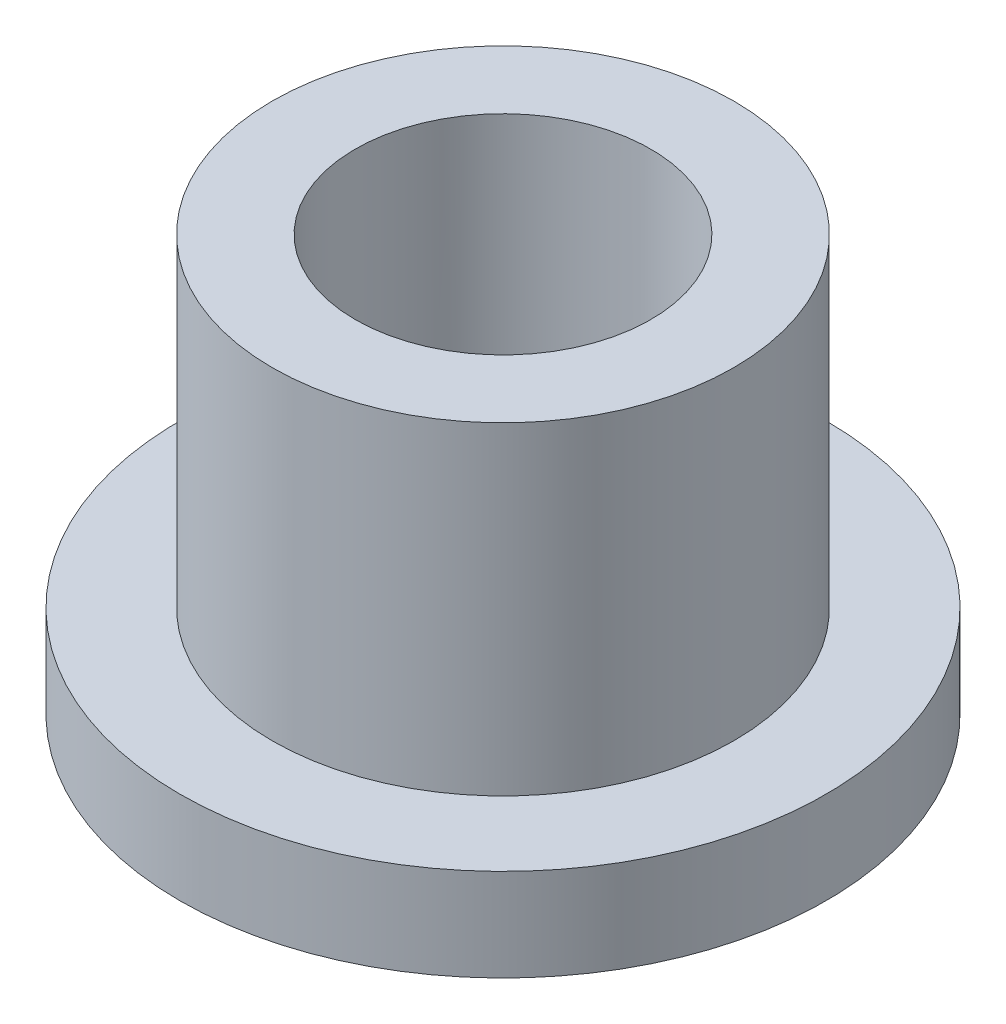
SolidWorks part; units mm, degrees
material "ABS"
ref_plane "Front Plane" through (0, 0, 0) normal (0, 0, 1) x (1, 0, 0)
ref_plane "Top Plane" through (0, 0, 0) normal (0, 1, 0) x (1, 0, 0)
ref_plane "Right Plane" through (0, 0, 0) normal (1, 0, 0) x (0, 0, -1)
sketch "Sketch2" plane through (0, 0, 0) normal (0, 0, 1) x (1, 0, 0)
  line L0 (1.6, 0) -> (1.6, 4.5)
  line L1 (1.6, 4.5) -> (2.5, 4.5)
  line L2 (2.5, 4.5) -> (2.5, 1)
  line L3 (2.5, 1) -> (3.5, 1)
  line L4 (3.5, 1) -> (3.5, 0)
  line L5 (3.5, 0) -> (1.6, 0)
  line L6 (0, -0.92) -> (0, -2.6933) construction
  dimension "D1" = 2.5
  dimension "D2" = 1.6
  dimension "D3" = 4.5
  dimension "D4" = 1
  dimension "D5" = 3.5
revolve "Revolve1" add sketch "Sketch2" angle 360 about L6
sketch "Sketch3" plane through (0, 0, 0) normal (0, -1, 0) x (1, 0, 0)
  circle A0 centre (0, 0) radius 2.5
  dimension "D1" = 5
extrude "Cut-Extrude1" cut sketch "Sketch3" against normal blind 0.5
